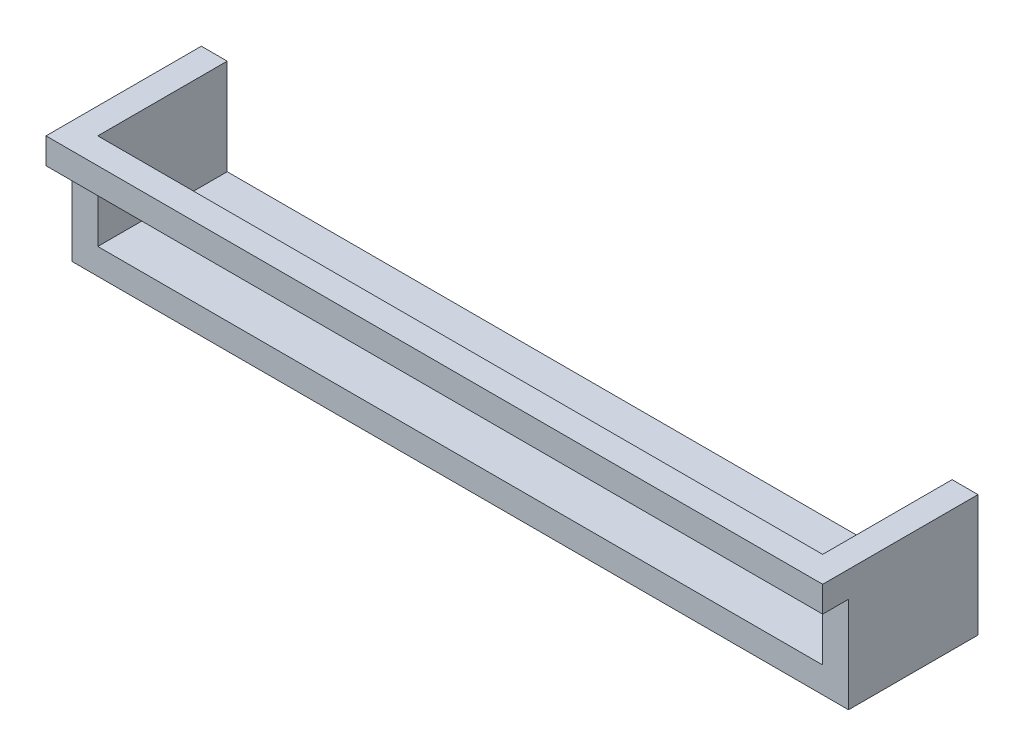
SolidWorks part; units mm, degrees
ref_plane "Спереди" through (0, 0, 0) normal (0, 0, 1) x (1, 0, 0)
ref_plane "Сверху" through (0, 0, 0) normal (0, 1, 0) x (1, 0, 0)
ref_plane "Справа" through (0, 0, 0) normal (1, 0, 0) x (0, 0, -1)
ref_plane "Плоскость4"
sketch "Эскиз1" plane through (0, 0, 0) normal (0, 1, 0) x (-1, 0, 0)
  line L0 (300, 50) -> (-300, 50)
  line L1 (-300, 50) -> (-300, -50)
  line L2 (-300, -50) -> (300, -50)
  line L3 (300, -50) -> (300, 50)
  dimension "D1" = 600
  dimension "D2" = 100
extrude "Выдавливание1" add sketch "Эскиз1" along normal blind 20
sketch "Эскиз2" plane through (0, 20, 0) normal (0, 1, 0) x (-1, 0, 0)
  line L0 (280, 50) -> (280, -50)
  line L1 (280, -50) -> (300, -50)
  line L2 (300, -50) -> (300, 50)
  line L3 (300, 50) -> (280, 50)
  line L4 (-300, 50) -> (-300, -50)
  line L5 (-300, -50) -> (-280, -50)
  line L6 (-280, -50) -> (-280, 50)
  line L7 (-280, 50) -> (-300, 50)
  line M2 (300, -50) -> (300, 50)
  line M3 (300, 50) -> (-300, 50)
  line M4 (-300, 50) -> (-300, -50)
  line M5 (-300, -50) -> (300, -50)
  dimension "D1" = 580
extrude "Выдавливание2" add sketch "Эскиз2" along normal blind 74 contours L6 M5 M3 M4 | L0 M3 M5 M2
ref_plane "Плоскость5"
sketch "Эскиз3" plane through (0, 0, 0) normal (1, 0, 0) x (0, 1, 0)
  line L0 (94, 70) -> (74, 70)
  line L1 (74, 70) -> (74, 50)
  line L2 (74, 50) -> (94, 50)
  line L3 (94, 50) -> (94, 70)
  dimension "D1" = 20
extrude "Выдавливание3" add sketch "Эскиз3" along normal blind 300 and the other way blind 300
